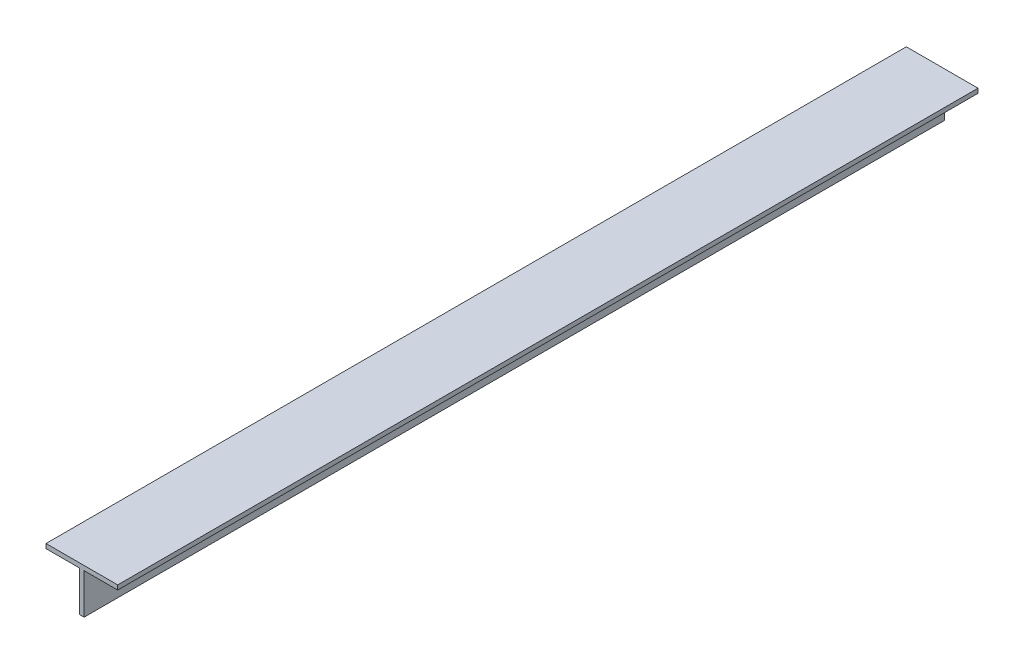
SolidWorks part; units mm, degrees
ref_plane "Front" through (0, 0, 0) normal (0, 0, 1) x (1, 0, 0)
ref_plane "Top" through (0, 0, 0) normal (0, 1, 0) x (1, 0, 0)
ref_plane "Right" through (0, 0, 0) normal (1, 0, 0) x (0, 0, -1)
sketch "Sketch1" plane through (0, 0, 0) normal (0, 0, 1) x (1, 0, 0)
  line L0 (-25.4, 31.75) -> (-25.4, 28.575)
  line L1 (-25.4, 28.575) -> (-1.5875, 28.575)
  line L2 (-1.5875, 28.575) -> (-1.5875, 0)
  line L3 (-1.5875, 0) -> (1.5875, 0)
  line L4 (1.5875, 0) -> (1.5875, 28.575)
  line L5 (1.5875, 28.575) -> (25.4, 28.575)
  line L6 (25.4, 28.575) -> (25.4, 31.75)
  line L7 (25.4, 31.75) -> (-25.4, 31.75)
  dimension "Thickness" = 3.175
  dimension "Width" = 50.8
  dimension "Height" = 31.75
extrude "Boss-Extrude1" add sketch "Sketch1" along normal mid plane 609.6
sketch "Sketch2" plane through (1.5875, 0, 0) normal (1, 0, 0) x (0, 0, -1)
  line L0 (0, 15.875) -> (0, 147.1907) construction
  line L1 (-304.8, 28.575) -> (304.8, 28.575) construction
  circle A0 centre (-200, 15.875) radius 3.5
  circle A1 centre (200, 15.875) radius 3.5
  dimension "D1" = 7
  dimension "D3" = 12.7
  dimension "D2" = 12.7
extrude "Cut-Extrude1" cut sketch "Sketch2" against normal through all
